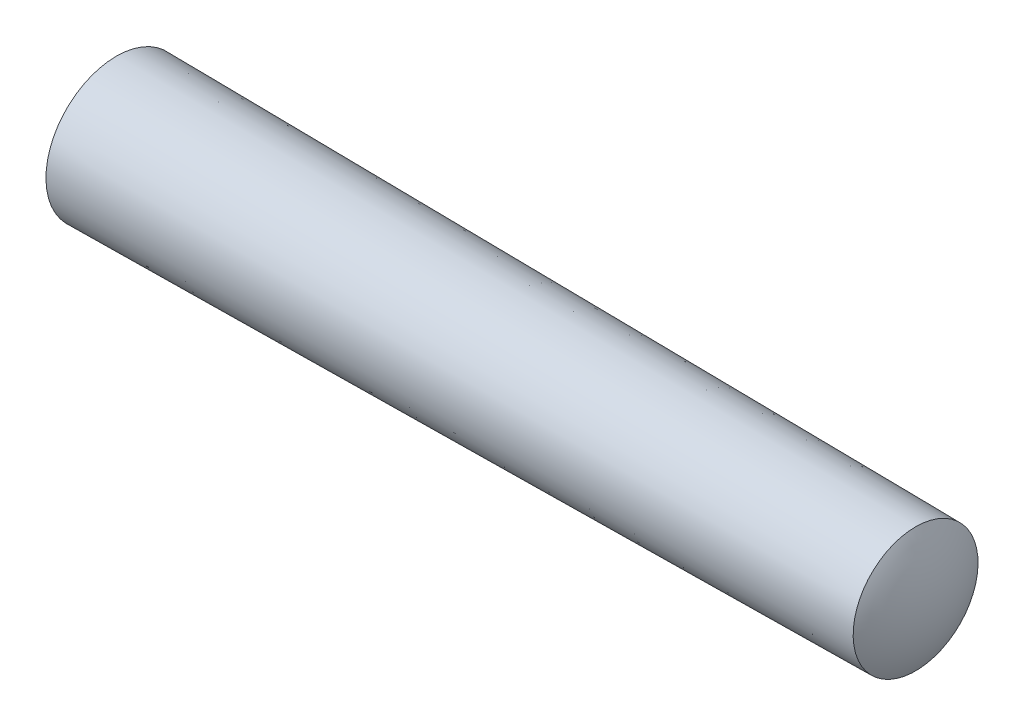
SolidWorks part; units mm, degrees
ref_plane "Přední rovina" through (0, 0, 0) normal (0, 0, 1) x (1, 0, 0)
ref_plane "Vrchní rovina" through (0, 0, 0) normal (0, 1, 0) x (1, 0, 0)
ref_plane "Pravá rovina" through (0, 0, 0) normal (1, 0, 0) x (0, 0, -1)
sketch "Skica1" plane through (0, 0, 0) normal (0, 0, 1) x (1, 0, 0)
  line L0 (0, 0) -> (0, 0.3384) construction
  line L1 (0, 0.3384) -> (3.84, 0.3)
  line L2 (3.84, 0.3) -> (3.84, 0) construction
  line L3 (3.84, 0) -> (0, 0)
  line L4 (3.84, 0) -> (3.92, 0) construction
  line L5 (-0.08, 0) -> (0, 0)
  line L6 (3.84, 0) -> (3.92, 0)
  arc A0 (3.84, 0.3) -> (3.92, 0) centre (3.3175, 0) cw
  arc A1 (0, 0.3384) -> (-0.08, 0) centre (0.6757, 0) ccw
  dimension "D1" = 0.08
  dimension "D2" = 0.6768
  dimension "a" = 0.08
  dimension "l" = 4
  dimension "d" = 0.6
revolve "Otočit kolem osy1" add sketch "Skica1" angle 360 about L3
equation "\"D1@Skica1\" = \"a@Skica1\""
equation "\"D2@Skica1\" =  (  ( \"l@Skica1\" - 2*\"a@Skica1\" )  / 50 )  + \"d@Skica1\""
